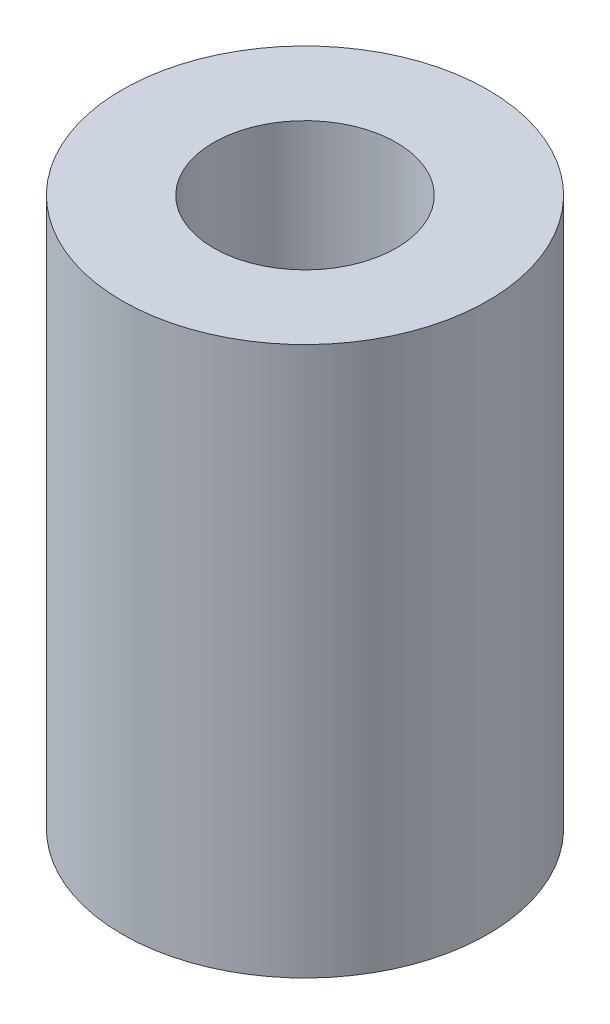
SolidWorks part; units mm, degrees
ref_plane "Front" through (0, 0, 0) normal (0, 0, 1) x (1, 0, 0)
ref_plane "Top" through (0, 0, 0) normal (0, 1, 0) x (1, 0, 0)
ref_plane "Right" through (0, 0, 0) normal (1, 0, 0) x (0, 0, -1)
sketch "Sketch1" plane through (0, 0, 0) normal (0, 1, 0) x (1, 0, 0)
  circle A0 centre (0, 0) radius 2.5
  circle A1 centre (0, 0) radius 5
  dimension "D1" = 5
  dimension "D2" = 10
extrude "Boss-Extrude1" add sketch "Sketch1" along normal blind 15
